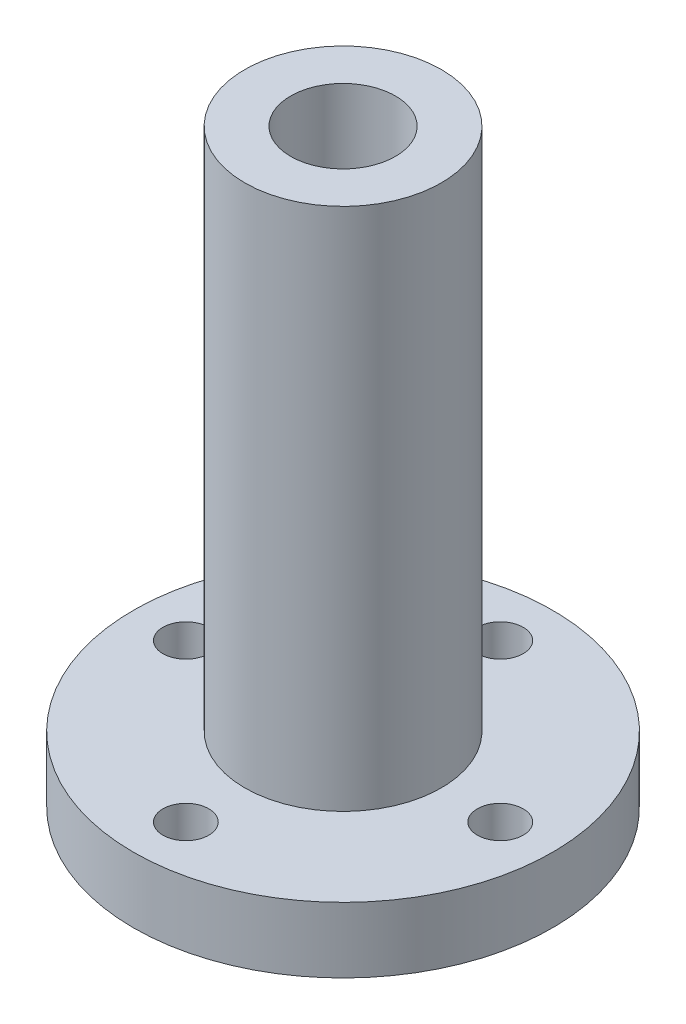
SolidWorks part; units mm, degrees
material "锌合金 7; AG40B; Zn-4Al-0.015Mg"
ref_plane "前视基准面" through (0, 0, 0) normal (0, 0, 1) x (1, 0, 0)
ref_plane "上视基准面" through (0, 0, 0) normal (0, 1, 0) x (1, 0, 0)
ref_plane "右视基准面" through (0, 0, 0) normal (1, 0, 0) x (0, 0, -1)
sketch "草图1" plane through (0, 0, 0) normal (0, 1, 0) x (1, 0, 0)
  line L0 (-1000, 0) -> (49000, 0) construction
  line L1 (0, -1000) -> (0, 49000) construction
  circle A0 centre (0, 0) radius 4
  circle A1 centre (0, 0) radius 16
  circle A2 centre (0, 0) radius 12 construction
  circle A3 centre (0, 12) radius 1.75
  circle A4 centre (-12, 0) radius 1.75
  circle A5 centre (12, 0) radius 1.75
  circle A6 centre (0, -12) radius 1.75
  dimension "D1" = 32
  dimension "D2" = 8
  dimension "D3" = 24
  dimension "D4" = 3.5
  dimension "D5" = 3.5
  dimension "D6" = 3.5
  dimension "D7" = 3.5
extrude "凸台-拉伸1" add sketch "草图1" along normal blind 5
sketch "草图2" plane through (0, 5, 0) normal (0, 1, 0) x (1, 0, 0)
  circle A0 centre (0, 0) radius 4 construction
  circle A1 centre (0, 0) radius 4
  circle A2 centre (0, 0) radius 7.5
  dimension "D1" = 15
extrude "凸台-拉伸2" add sketch "草图2" along normal blind 40
